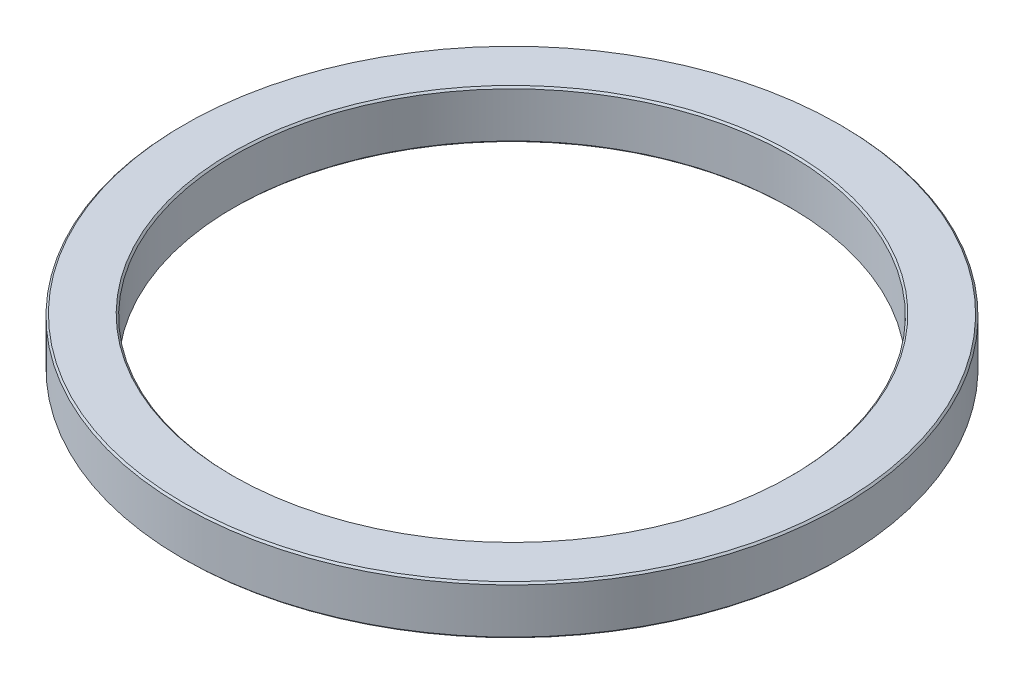
SolidWorks part; units mm, degrees
ref_plane "前视基准面" through (0, 0, 0) normal (0, 0, 1) x (1, 0, 0)
ref_plane "上视基准面" through (0, 0, 0) normal (0, 1, 0) x (1, 0, 0)
ref_plane "右视基准面" through (0, 0, 0) normal (1, 0, 0) x (0, 0, -1)
other "Configuration Table"
sketch "草图1" plane through (0, 0, 0) normal (0, 1, 0) x (1, 0, 0)
  circle A0 centre (0, 0) radius 80.1
  circle A1 centre (0, 0) radius 94.9
  dimension "D1" = 160.2
  dimension "D2" = 189.8
extrude "凸台-拉伸1" add sketch "草图1" along normal blind 14
chamfer "倒角1" distance 0.5 angle 45 4 edges at (0, 0, 80.1) (0, 0, 94.9) (0, 14, 94.9) (0, 14, 80.1)
